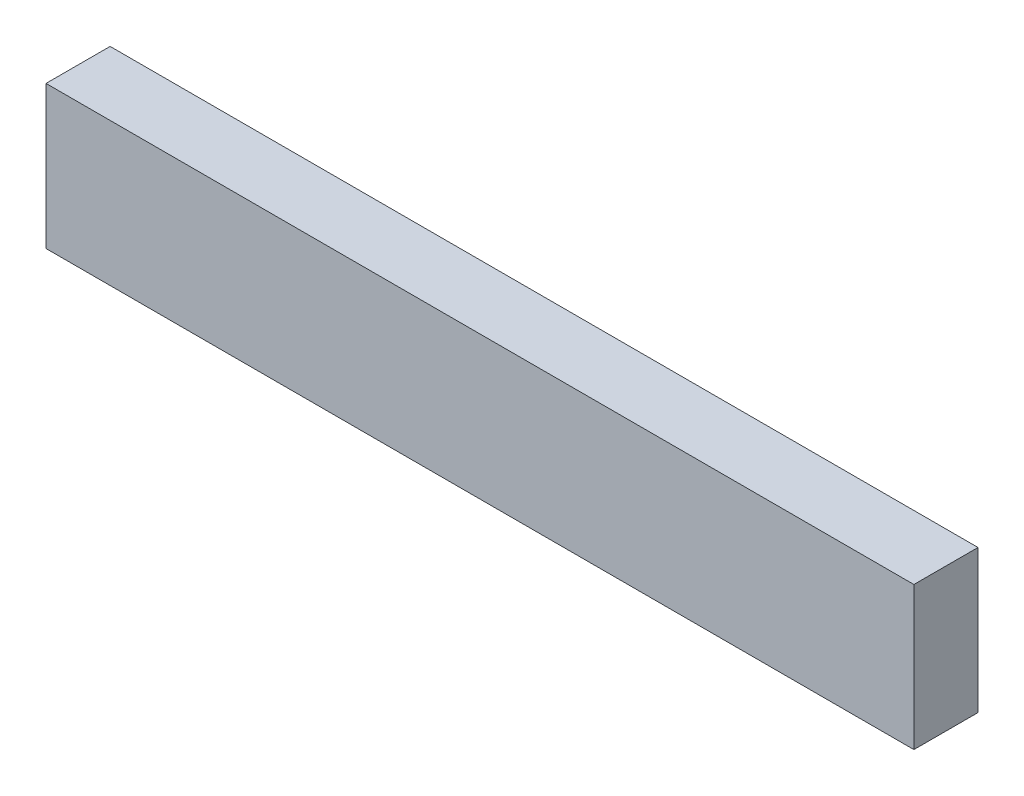
SolidWorks part; units mm, degrees
ref_plane "Front Plane" through (0, 0, 0) normal (0, 0, 1) x (1, 0, 0)
ref_plane "Top Plane" through (0, 0, 0) normal (0, 1, 0) x (1, 0, 0)
ref_plane "Right Plane" through (0, 0, 0) normal (1, 0, 0) x (0, 0, -1)
sketch "Sketch3" plane through (0, 0, 0) normal (0, 1, 0) x (1, 0, 0)
  line L1 (0, 0) -> (67.056, 0)
  line L2 (0, 0) -> (0, 4.953)
  line L3 (0, 4.953) -> (67.056, 4.953)
  line L4 (67.056, 0) -> (67.056, 4.953)
  dimension "D1" = 67.056
  dimension "D2" = 4.953
extrude "Boss-Extrude1" add sketch "Sketch3" along normal blind 11.049
